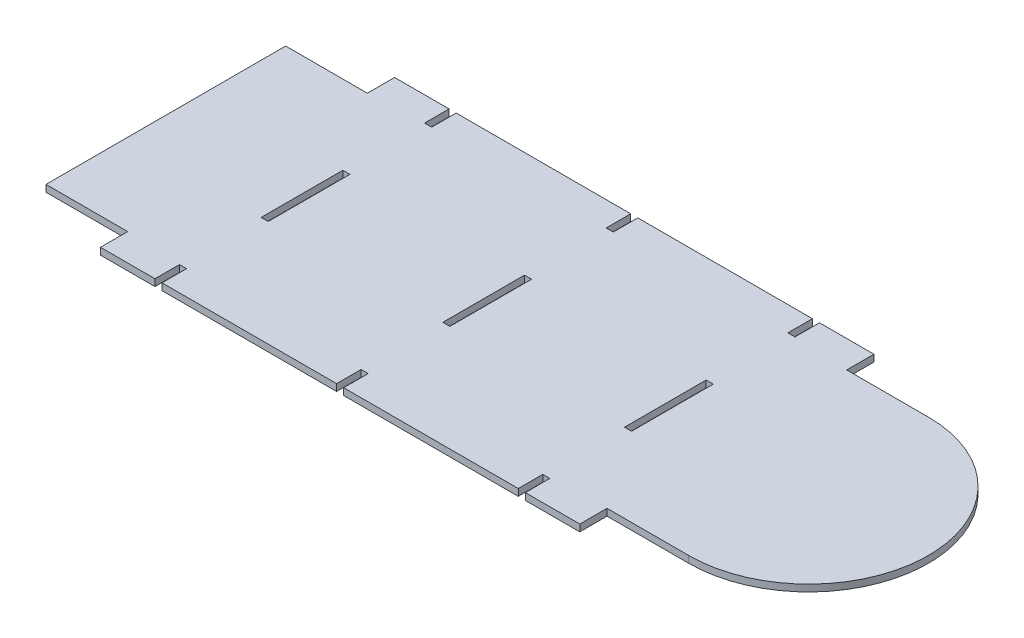
SolidWorks part; units mm, degrees
ref_plane "Front Plane" through (0, 0, 0) normal (0, 0, 1) x (1, 0, 0)
ref_plane "Top Plane" through (0, 0, 0) normal (0, 1, 0) x (1, 0, 0)
ref_plane "Right Plane" through (0, 0, 0) normal (1, 0, 0) x (0, 0, -1)
sketch "Sketch1" plane through (0, 0, 0) normal (0, 1, 0) x (1, 0, 0)
  line L0 (-145.1006, 0) -> (-86.36, 0) construction
  line L1 (0, 93.8961) -> (0, -87.2891) construction
  line L2 (-149.86, -55.88) -> (-149.86, 55.88)
  line L3 (-149.86, 55.88) -> (-111.76, 55.88)
  line L4 (-111.76, 55.88) -> (-111.76, 68.58)
  line L5 (-111.76, 68.58) -> (-86.36, 68.58)
  line L6 (-1.651, 68.58) -> (-1.651, 57.15)
  line L7 (-1.651, 57.15) -> (1.651, 57.15)
  line L8 (-86.36, 68.58) -> (-86.36, 57.15)
  line L9 (-86.36, 57.15) -> (-83.058, 57.15)
  line L10 (-83.058, 57.15) -> (-83.058, 68.58)
  line L11 (-83.058, 68.58) -> (-1.651, 68.58)
  line L12 (-83.058, 0) -> (162.6347, 0) construction
  line L13 (1.651, 19.05) -> (-1.651, 19.05)
  line L14 (-86.36, -19.05) -> (-86.36, 19.05)
  line L15 (-86.36, 19.05) -> (-83.058, 19.05)
  line L16 (-83.058, -19.05) -> (-83.058, 19.05)
  line L17 (-1.651, 19.05) -> (-1.651, -19.05)
  line L18 (83.058, -19.05) -> (83.058, 19.05)
  line L19 (86.36, 19.05) -> (83.058, 19.05)
  line L20 (86.36, -19.05) -> (86.36, 19.05)
  line L21 (1.651, 19.05) -> (1.651, -19.05)
  line L22 (1.651, 68.58) -> (1.651, 57.15)
  line L23 (83.058, 68.58) -> (1.651, 68.58)
  line L24 (83.058, 57.15) -> (83.058, 68.58)
  line L25 (86.36, 57.15) -> (83.058, 57.15)
  line L26 (86.36, 68.58) -> (86.36, 57.15)
  line L27 (111.76, 68.58) -> (86.36, 68.58)
  line L28 (111.76, 55.88) -> (111.76, 68.58)
  line L29 (149.86, 55.88) -> (111.76, 55.88)
  line L31 (86.36, -57.15) -> (83.058, -57.15)
  line L32 (86.36, -68.58) -> (86.36, -57.15)
  line L33 (111.76, -68.58) -> (86.36, -68.58)
  line L34 (111.76, -55.88) -> (111.76, -68.58)
  line L35 (149.86, -55.88) -> (111.76, -55.88)
  line L36 (86.36, -19.05) -> (83.058, -19.05)
  line L37 (1.651, -19.05) -> (-1.651, -19.05)
  line L38 (83.058, -68.58) -> (1.651, -68.58)
  line L39 (1.651, -68.58) -> (1.651, -57.15)
  line L40 (-1.651, -57.15) -> (1.651, -57.15)
  line L41 (-1.651, -68.58) -> (-1.651, -57.15)
  line L42 (-83.058, -68.58) -> (-1.651, -68.58)
  line L43 (-83.058, -57.15) -> (-83.058, -68.58)
  line L44 (-86.36, -57.15) -> (-83.058, -57.15)
  line L45 (-86.36, -68.58) -> (-86.36, -57.15)
  line L46 (-111.76, -68.58) -> (-86.36, -68.58)
  line L47 (-111.76, -55.88) -> (-111.76, -68.58)
  line L48 (-149.86, -55.88) -> (-111.76, -55.88)
  line L49 (-86.36, -19.05) -> (-83.058, -19.05)
  line L50 (83.058, -57.15) -> (83.058, -68.58)
  arc A0 (149.86, -55.88) -> (149.86, 55.88) centre (149.86, 0) ccw
  point P11 (-86.36, 68.58)
  point P27 (83.058, 0)
  point P30 (0, 19.05)
  point P31 (0, 57.15)
  point P46 (149.86, 0)
  point P48 (86.36, 0)
  point P49 (1.651, 0)
  point P50 (-1.651, 0)
  point P62 (-149.86, 0)
extrude "Boss-Extrude1" add sketch "Sketch1" along normal blind 3.175
sketch "Sketch2" plane through (-149.86, 0, 0) normal (-1, 0, 0) x (0, 0, 1)
  line L0 (0, 21.9161) -> (0, -12.6356) construction
  circle A0 centre (0, 1.5558) radius 0.6278
  point P3 (0, 1.5558)
extrude "Cut-Extrude1" cut sketch "Sketch2" against normal blind 2.54
